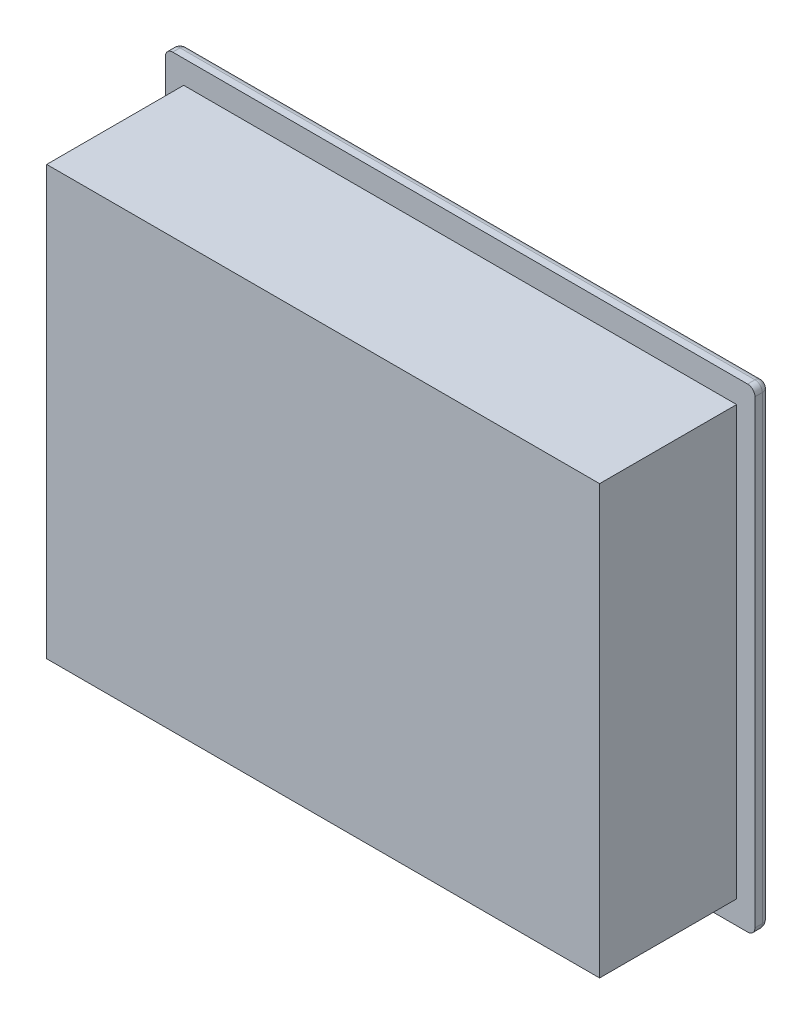
SolidWorks part; units mm, degrees
material "PVC 0.007 塑化"
ref_plane "前视基准面" through (0, 0, 0) normal (0, 0, 1) x (1, 0, 0)
ref_plane "上视基准面" through (0, 0, 0) normal (0, 1, 0) x (1, 0, 0)
ref_plane "右视基准面" through (0, 0, 0) normal (1, 0, 0) x (0, 0, -1)
sketch "草图1" plane through (0, 0, 0) normal (0, 0, 1) x (1, 0, 0)
  line L1 (-120.5, -97) -> (120.5, -97)
  line L2 (-120.5, -97) -> (-120.5, 97)
  line L3 (-120.5, 97) -> (120.5, 97)
  line L4 (120.5, -97) -> (120.5, 97)
  line L5 (-120.5, -97) -> (120.5, 97) construction
  line L6 (-120.5, 97) -> (120.5, -97) construction
  point P0 (0, 0)
  dimension "D1" = 194
  dimension "D2" = 241
extrude "凸台-拉伸1" add sketch "草图1" along normal blind 6
sketch "草图2" plane through (0, 0, 6) normal (0, 0, 1) x (1, 0, 0)
  line L1 (-113, -87.5) -> (113, -87.5)
  line L2 (-113, -87.5) -> (-113, 87.5)
  line L3 (-113, 87.5) -> (113, 87.5)
  line L4 (113, -87.5) -> (113, 87.5)
  line L5 (-113, -87.5) -> (113, 87.5) construction
  line L6 (-113, 87.5) -> (113, -87.5) construction
  point P0 (0, 0)
  dimension "D1" = 226
  dimension "D2" = 175
extrude "凸台-拉伸2" add sketch "草图2" along normal blind 56
fillet "圆角1" radius 3 8 edges at (120.5, 97, 3) (120.5, -97, 3) (-120.5, -97, 3) (-120.5, 97, 3) (-120.5, 0, 0) (0, -97, 0) (120.5, 0, 0) (0, 97, 0)
sketch "草图3" plane through (0, 0, 0) normal (0, 0, -1) x (-1, 0, 0)
  line L1 (-90, -70) -> (90, -70)
  line L2 (-90, -70) -> (-90, 70)
  line L3 (-90, 70) -> (90, 70)
  line L4 (90, -70) -> (90, 70)
  line L5 (-90, -70) -> (90, 70) construction
  line L6 (-90, 70) -> (90, -70) construction
  point P0 (0, 0)
  dimension "D1" = 180
  dimension "D2" = 140
extrude "切除-拉伸1" cut sketch "草图3" against normal blind 1
sketch "草图4" plane through (0, 0, 1) normal (0, 0, -1) x (-1, 0, 0)
  text T0 "GT2308" font "Century Gothic" height in points 42
extrude "凸台-拉伸3" add sketch "草图4" along normal blind 1
